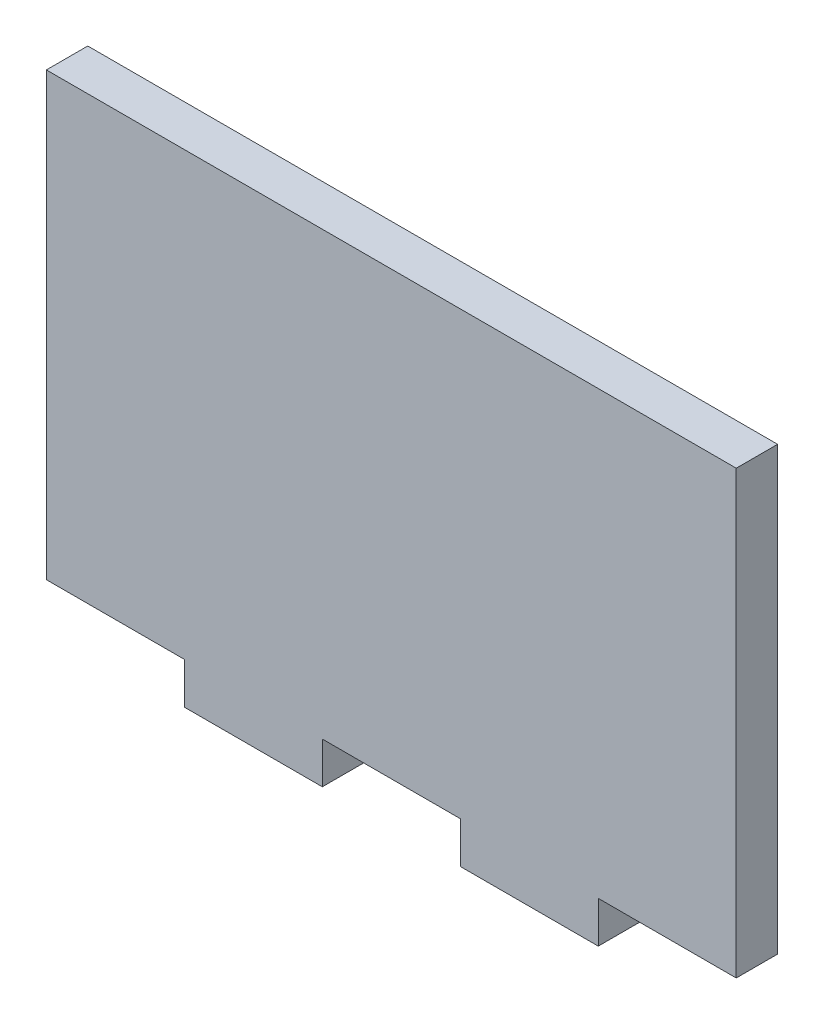
SolidWorks part; units mm, degrees
ref_plane "Plan de face" through (0, 0, 0) normal (0, 0, 1) x (1, 0, 0)
ref_plane "Plan de dessus" through (0, 0, 0) normal (0, 1, 0) x (1, 0, 0)
ref_plane "Plan de droite" through (0, 0, 0) normal (1, 0, 0) x (0, 0, -1)
sketch "Esquisse1" plane through (0, 0, 0) normal (0, 0, 1) x (1, 0, 0)
  line L1 (0, 0) -> (-100, 0)
  line L2 (0, 0) -> (0, 64)
  line L3 (0, 64) -> (-100, 64)
  line L4 (-100, 0) -> (-100, 64)
  dimension "D1" = 64
  dimension "D2" = 100
extrude "Boss.-Extru.1" add sketch "Esquisse1" along normal blind 6
sketch "Esquisse2" plane through (0, 0, 0) normal (0, -1, 0) x (1, 0, 0)
  line L0 (-100, 6) -> (0, 6) construction
  line L1 (-80, 6) -> (-60, 6)
  line L2 (-80, 6) -> (-80, 0)
  line L3 (-80, 0) -> (-60, 0)
  line L4 (-60, 6) -> (-60, 0)
  line L5 (-100, 0) -> (0, 0) construction
  line L6 (-100, 6) -> (-100, 0) construction
  line L7 (-40, 6) -> (-20, 6)
  line L8 (-40, 6) -> (-40, 0)
  line L9 (-40, 0) -> (-20, 0)
  line L10 (-20, 6) -> (-20, 0)
  dimension "D1" = 20
  dimension "D2" = 20
  dimension "D3" = 20
  dimension "D4" = 20
extrude "Boss.-Extru.2" add sketch "Esquisse2" along normal blind 6
